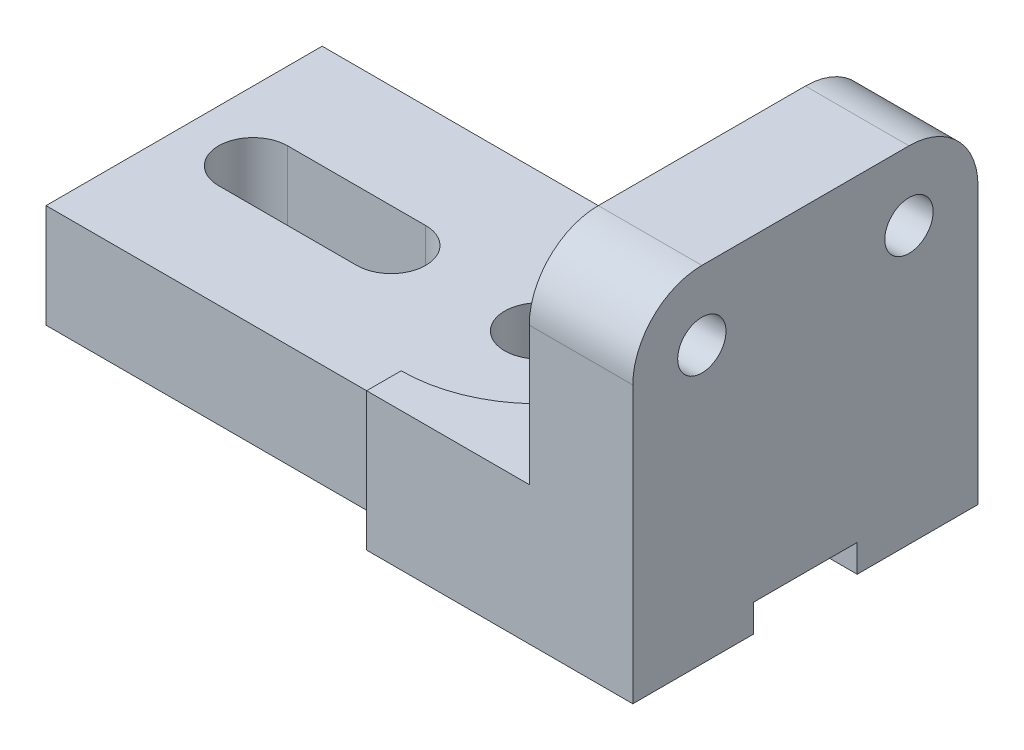
SolidWorks part; units mm, degrees
ref_plane "Ön Düzlem" through (0, 0, 0) normal (0, 0, 1) x (1, 0, 0)
ref_plane "Üst Düzlem" through (0, 0, 0) normal (0, 1, 0) x (1, 0, 0)
ref_plane "Sağ Düzlem" through (0, 0, 0) normal (1, 0, 0) x (0, 0, -1)
sketch "Çizim1" plane through (0, 0, 0) normal (0, 0, 1) x (1, 0, 0)
  line L1 (-7.1145, 27.6039) -> (7.8855, 27.6039)
  line L2 (-7.1145, 27.6039) -> (-7.1145, -7.3961)
  line L4 (7.8855, 27.6039) -> (7.8855, -22.3961)
  line L5 (7.8855, -22.3961) -> (-82.1145, -22.3961)
  line L7 (-7.1145, -7.3961) -> (-82.1145, -7.3961)
  line L8 (-82.1145, -22.3961) -> (-82.1145, -7.3961)
  dimension "D1" = 50
  dimension "D2" = 90
  dimension "D3" = 15
  dimension "D4" = 15
extrude "Yükseklik-Ekstrüzyon2" add sketch "Çizim1" along normal blind 50
sketch "Çizim2" plane through (0, -7.3961, 0) normal (0, 1, 0) x (1, 0, 0)
  line L0 (-7.1145, -50) -> (-82.1145, -50) construction
  line L1 (-7.1145, 0) -> (-30.671, 0)
  line L2 (-7.1145, 0) -> (-7.1145, -50)
  line L3 (-7.1145, -50) -> (-30.671, -50)
  line L4 (-30.671, 0) -> (-30.671, -5)
  line L7 (-30.671, -45) -> (-30.671, -50)
  arc A0 (-30.671, -45) -> (-30.671, -5) centre (-30.671, -25) ccw
  dimension "D1" = 40
extrude "Yükseklik-Ekstrüzyon3" add sketch "Çizim2" along normal blind 5
sketch "Çizim3" plane through (0, -7.3961, 0) normal (0, 1, 0) x (1, 0, 0)
  line L0 (-82.1145, -50) -> (-82.1145, 0) construction
  line L1 (-30.671, -5) -> (-82.1145, -5)
  line L2 (-30.671, -5) -> (-30.671, -45)
  line L3 (-30.671, -45) -> (-82.1145, -45)
  line L4 (-82.1145, -5) -> (-82.1145, -45)
  line L6 (-30.671, 0) -> (-82.1145, 0)
  line L7 (-30.671, 0) -> (-30.671, -50)
  line L8 (-30.671, -50) -> (-82.1145, -50)
  line L9 (-82.1145, 0) -> (-82.1145, -50)
  line M5 (-30.671, -5) -> (-30.671, 0)
  line M6 (-30.671, 0) -> (-82.1145, 0)
  line M7 (-82.1145, 0) -> (-82.1145, -50)
  line M8 (-82.1145, -50) -> (-30.671, -50)
  line M9 (-30.671, -50) -> (-30.671, -45)
extrude "Kes-Ekstrüzyon1" cut sketch "Çizim3" against normal blind 15 contours L1 M5 M6 M7 | L3 M9 M7 M8
sketch "Çizim4" plane through (-82.1145, 0, 0) normal (-1, 0, 0) x (0, 0, 1)
  line L0 (45, -22.3961) -> (5, -22.3961) construction
  line L1 (17.5, -22.3961) -> (32.5, -22.3961)
  line L2 (17.5, -22.3961) -> (17.5, -18.3961)
  line L3 (17.5, -18.3961) -> (32.5, -18.3961)
  line L4 (32.5, -22.3961) -> (32.5, -18.3961)
  line L5 (5, -22.3961) -> (5, -7.3961) construction
  dimension "D1" = 4
  dimension "D2" = 15
  dimension "D3" = 12.5
extrude "Kes-Ekstrüzyon2" cut sketch "Çizim4" against normal blind 90
fillet "Radyus2" radius 10 1 edges at (0.3855, 27.6039, 0)
fillet "Radyus3" radius 10 1 edges at (0.3855, 27.6039, 50)
sketch "Çizim5" plane through (-7.1145, 0, 0) normal (-1, 0, 0) x (0, 0, 1)
  circle A0 centre (10, 17.6039) radius 3.5
  circle A1 centre (40, 17.6039) radius 3.5
  dimension "D1" = 7
  dimension "D2" = 7
extrude "Kes-Ekstrüzyon3" cut sketch "Çizim5" against normal up to next contours A0 | A1
sketch "Çizim6" plane through (0, -7.3961, 0) normal (0, 1, 0) x (1, 0, 0)
  line L0 (-72.1145, -25) -> (-52.1145, -25) construction
  line L1 (-72.1145, -20) -> (-52.1145, -20)
  line L2 (-72.1145, -30) -> (-52.1145, -30)
  line L3 (-82.1145, -45) -> (-82.1145, -5) construction
  circle A0 centre (-30.671, -25) radius 5
  arc A1 (-72.1145, -20) -> (-72.1145, -30) centre (-72.1145, -25) ccw
  arc A2 (-52.1145, -30) -> (-52.1145, -20) centre (-52.1145, -25) ccw
  point P5 (-62.1145, -25)
  dimension "D1" = 10
  dimension "D4" = 5
  dimension "D2" = 10
  dimension "D3" = 20
extrude "Kes-Ekstrüzyon4" cut sketch "Çizim6" along normal through all and the other way through all
